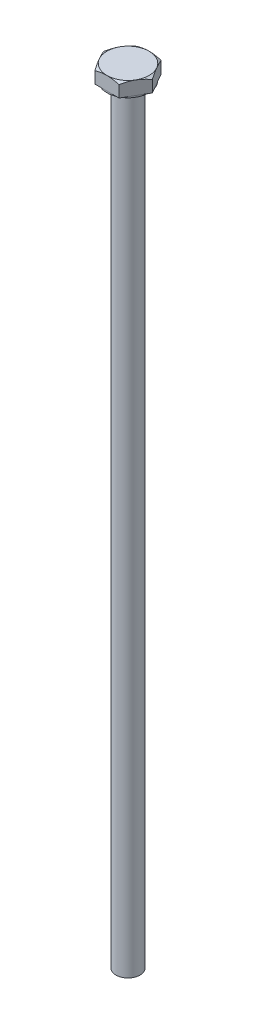
SolidWorks part; units mm, degrees
material "Steel Fastener"
ref_plane "FRONT" through (0, 0, 0) normal (0, 0, 1) x (1, 0, 0)
ref_plane "TOP" through (0, 0, 0) normal (0, 1, 0) x (1, 0, 0)
ref_plane "RIGHT" through (0, 0, 0) normal (1, 0, 0) x (0, 0, -1)
sketch "Sketch4" plane through (0, 0, 0) normal (0, 1, 0) x (1, 0, 0)
  line L0 (6.4158, 0) -> (3.2079, 5.5562)
  line L1 (3.2079, 5.5562) -> (-3.2079, 5.5562)
  line L2 (-3.2079, 5.5562) -> (-6.4158, 0)
  line L3 (-6.4158, 0) -> (-3.2079, -5.5562)
  line L4 (-3.2079, -5.5562) -> (3.2079, -5.5563)
  line L5 (3.2079, -5.5563) -> (6.4158, 0)
  circle A1 centre (0, 0) radius 5.5562 construction
  dimension "HEX SIZE" = 11.1125
  dimension "D1" = 120
extrude "Base-Extrude" add sketch "Sketch4" along normal blind 3.9688
sketch "Sketch5" plane through (0, 0, 0) normal (0, -1, 0) x (1, 0, 0)
  circle A0 centre (0, 0) radius 3.175
  dimension "DIAMETER" = 6.35
extrude "Boss-Extrude1" add sketch "Sketch5" along normal blind 203.2
sketch "Sketch8" plane through (0, 0, 0) normal (1, 0, 0) x (0, 0, -1)
  line L0 (5.5562, 3.9688) -> (11.7264, 0.4064)
  line L1 (5.5562, 3.9688) -> (5.5562, 0) construction
  line L2 (14.2664, 3.9688) -> (5.5562, 3.9688)
  line L3 (0, 0) -> (0, 23.3235) construction
  line L4 (0, -203.2) -> (0, 0) construction
  line L5 (5.5562, 0) -> (14.2664, 0)
  line L6 (5.5562, 0) -> (5.5562, 0.4064)
  line L7 (0, 3.9688) -> (5.5562, 3.9688) construction
  line L11 (14.2664, 3.9688) -> (14.2664, 0)
  line L13 (11.7264, 0.4064) -> (5.5562, 0.4064)
  dimension "D1" = 30
  dimension "D2" = 0.4064
  dimension "D3" = 2.54
revolve "Cut-Revolve1" cut sketch "Sketch8" angle 360 about L3
chamfer "Chamfer1" distance 0.635 angle 30 1 edges at (0, -203.2, -3.175)
ref_plane "THREADS" through (0, -184.15, 0) normal (0, -1, 0) x (1, 0, 0)
sketch "Sketch9" plane through (-0.2014, -4.2299, 5.5562) normal (0, 0, 1) x (1, 0, 0)
  line L2 (5.0132, 8.1986) -> (0.2014, 8.1986) construction
  line L3 (0.2014, -45.7701) -> (0.2014, 54.2299) construction
  circle A0 centre (0.2014, 6.2174) radius 0.7938
  dimension "D1" = 1.5875
  dimension "D2" = 1.9812
extrude "drilledhead" [suppressed] cut sketch "Sketch9" against normal through all
equation "\"D1@Chamfer1\"=.1*\"DIAMETER@Sketch5\""
equation "\"THREAD LENGTH@THREADS\"=2*\"DIAMETER@Sketch5\"+.25"
